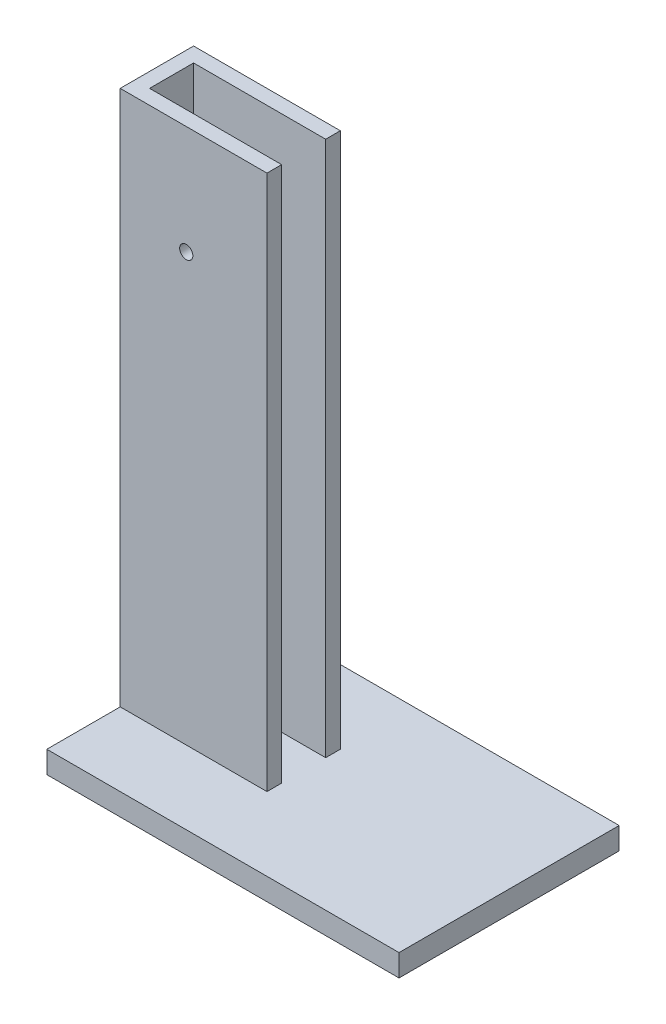
SolidWorks part; units mm, degrees
material "1023 Carbon Steel Sheet (SS)"
ref_plane "Front Plane" through (0, 0, 0) normal (0, 0, 1) x (1, 0, 0)
ref_plane "Top Plane" through (0, 0, 0) normal (0, 1, 0) x (1, 0, 0)
ref_plane "Right Plane" through (0, 0, 0) normal (1, 0, 0) x (0, 0, -1)
sketch "Sketch1" plane through (0, 0, 0) normal (0, 1, 0) x (1, 0, 0)
  line L0 (-80, 30) -> (100, 30)
  line L1 (-100, -50) -> (100, -50)
  line L2 (-100, -50) -> (-100, 50)
  line L3 (-100, 50) -> (100, 50)
  line L5 (-100, -50) -> (100, 50) construction
  line L6 (-100, 50) -> (100, -50) construction
  line L8 (-80, -30) -> (100, -30)
  line L9 (-80, -30) -> (-80, 30)
  line L13 (100, -50) -> (100, -30)
  line L14 (100, 50) -> (100, 30)
  point P0 (0, 0)
  dimension "D4" = 20
  dimension "D1" = 100
  dimension "D2" = 200
  dimension "D3" = 20
extrude "Boss-Extrude1" add sketch "Sketch1" along normal blind 730
sketch "Sketch2" plane through (0, 0, 0) normal (0, -1, 0) x (1, 0, 0)
  line L0 (-100, 50) -> (100, 50) construction
  line L1 (-100, -150) -> (380, -150)
  line L2 (-100, -150) -> (-100, 150)
  line L3 (-100, 150) -> (380, 150)
  line L4 (380, -150) -> (380, 150)
  point P0 (0, 0)
  point P5 (145, 75)
  dimension "D1" = 100
  dimension "D2" = 100
  dimension "D3" = 280
extrude "Boss-Extrude2" add sketch "Sketch2" along normal blind 30 separate body
sketch "Sketch5" plane through (0, 0, 30) normal (0, 0, -1) x (-1, 0, 0)
  line L1 (-100, 730) -> (100, 730) construction
  line L2 (100, 730) -> (100, 0) construction
  circle A0 centre (10, 581.9) radius 9
  dimension "D1" = 18
  dimension "D2" = 90
  dimension "D3" = 148.1
extrude "Cut-Extrude1" cut sketch "Sketch5" against normal blind 23 and the other way blind 29
